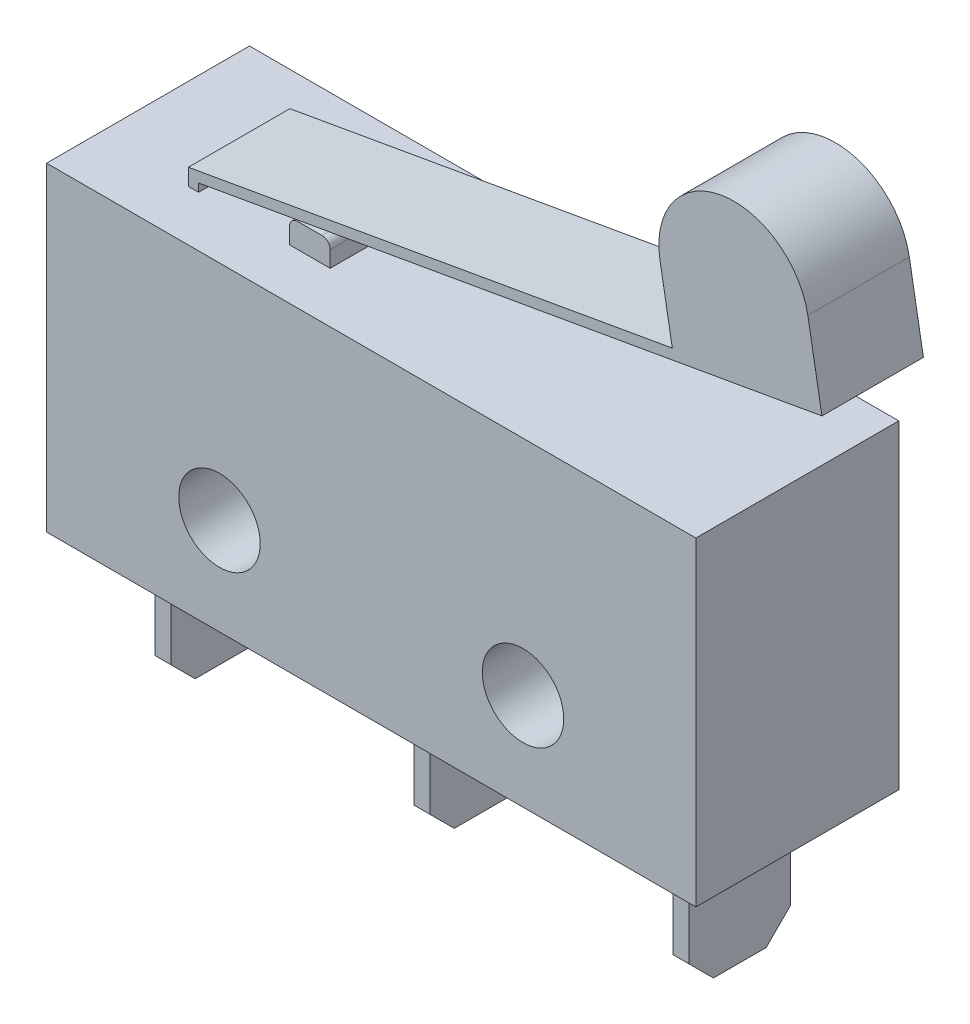
SolidWorks part; units mm, degrees
ref_plane "Front Plane" through (0, 0, 0) normal (0, 0, 1) x (1, 0, 0)
ref_plane "Top Plane" through (0, 0, 0) normal (0, 1, 0) x (1, 0, 0)
ref_plane "Right Plane" through (0, 0, 0) normal (1, 0, 0) x (0, 0, -1)
sketch "Sketch1" plane through (0, 0, 0) normal (0, 1, 0) x (1, 0, 0)
  line L1 (-10.16, -3.175) -> (10.16, -3.175)
  line L2 (-10.16, -3.175) -> (-10.16, 3.175)
  line L3 (-10.16, 3.175) -> (10.16, 3.175)
  line L4 (10.16, -3.175) -> (10.16, 3.175)
  line L5 (-10.16, -3.175) -> (10.16, 3.175) construction
  line L6 (-10.16, 3.175) -> (10.16, -3.175) construction
  point P0 (0, 0)
  dimension "D1" = 20.32
  dimension "D2" = 6.35
extrude "Boss-Extrude1" add sketch "Sketch1" along normal blind 10
sketch "Sketch2" plane through (0, 0, 0) normal (0, 0, 1) x (1, 0, 0)
  line L0 (-4.1425, 10) -> (-4.1425, 10.508)
  line L1 (-10.16, 10) -> (10.16, 10) construction
  line L2 (-3.8885, 10.762) -> (-3.1265, 10.762)
  line L3 (-2.8725, 10.508) -> (-2.8725, 10)
  line L4 (-4.1425, 10) -> (-2.8725, 10)
  line L5 (-7.31, 10) -> (-7.31, 10.5204)
  line L6 (-7.31, 10.5204) -> (7.8358, 13.191)
  line L7 (7.8358, 13.191) -> (7.4498, 15.3798)
  line L9 (12.0774, 16.1957) -> (12.5185, 13.6943)
  line L10 (12.5185, 13.6943) -> (-6.9925, 10.254)
  line L11 (-6.9925, 10.254) -> (-6.9925, 10)
  line L12 (-6.9925, 10) -> (-7.31, 10)
  line L13 (-4.1425, 10) -> (-10.16, 10) construction
  line L14 (7.8358, 13.191) -> (7.8909, 12.8783) construction
  line L15 (-8.36, 0) -> (-8.36, -4)
  line L16 (-10.16, 0) -> (10.16, 0) construction
  line L17 (-8.36, -4) -> (-7.86, -4)
  line L18 (-7.86, -4) -> (-7.86, 0)
  line L19 (-7.86, 0) -> (-8.36, 0)
  line L20 (-0.25, 0) -> (0.25, 0)
  line L21 (0.25, 0) -> (0.25, -4)
  line L22 (0.25, -4) -> (-0.25, -4)
  line L23 (-0.25, -4) -> (-0.25, 0)
  line L24 (8.36, 0) -> (7.86, 0)
  line L25 (7.86, 0) -> (7.86, -4)
  line L26 (7.86, -4) -> (8.36, -4)
  line L27 (8.36, -4) -> (8.36, 0)
  line L28 (-10.16, 10) -> (-10.16, 0) construction
  line L29 (10.16, 10) -> (10.16, 0) construction
  arc A0 (-3.1265, 10.762) -> (-2.8725, 10.508) centre (-3.1265, 10.508) cw
  arc A1 (-4.1425, 10.508) -> (-3.8885, 10.762) centre (-3.8885, 10.508) cw
  arc A2 (12.0774, 16.1957) -> (7.4498, 15.3798) centre (9.7636, 15.7877) ccw
  point P16 (-2.8725, 10.762)
  point P19 (-4.1425, 10.762)
  point P23 (-7.1513, 10)
  dimension "D3" = 0.254
  dimension "D7" = 2.3495
  dimension "D1" = 1.27
  dimension "D2" = 0.762
  dimension "D5" = 0.3175
  dimension "D6" = 0.254
  dimension "D8" = 19.812
  dimension "D9" = 100
  dimension "D10" = 2.54
  dimension "D11" = 4
  dimension "D12" = 1.8
  dimension "D13" = 0.5
  dimension "D14" = 1.8
  dimension "D15" = 2.85
extrude "Boss-Extrude2" add sketch "Sketch2" along normal mid plane 3.175
chamfer "Chamfer1" distance 0.762 angle 45 6 edges at (-8.11, -4, -1.5875) (0, -4, -1.5875) (8.11, -4, -1.5875) (8.11, -4, 1.5875) (0, -4, 1.5875) (-8.11, -4, 1.5875)
sketch "Sketch3" plane through (0, 0, 3.175) normal (0, 0, 1) x (1, 0, 0)
  line L0 (-4.75, 3.025) -> (4.75, 3.025) construction
  line L1 (4.75, 1.75) -> (4.75, 0) construction
  line L2 (-10.16, 0) -> (10.16, 0) construction
  circle A0 centre (-4.75, 3.025) radius 1.275
  circle A1 centre (4.75, 3.025) radius 1.275
  point P4 (0, 3.025)
  dimension "D1" = 2.55
  dimension "D2" = 9.5
  dimension "D3" = 1.75
extrude "Cut-Extrude1" cut sketch "Sketch3" against normal through all
